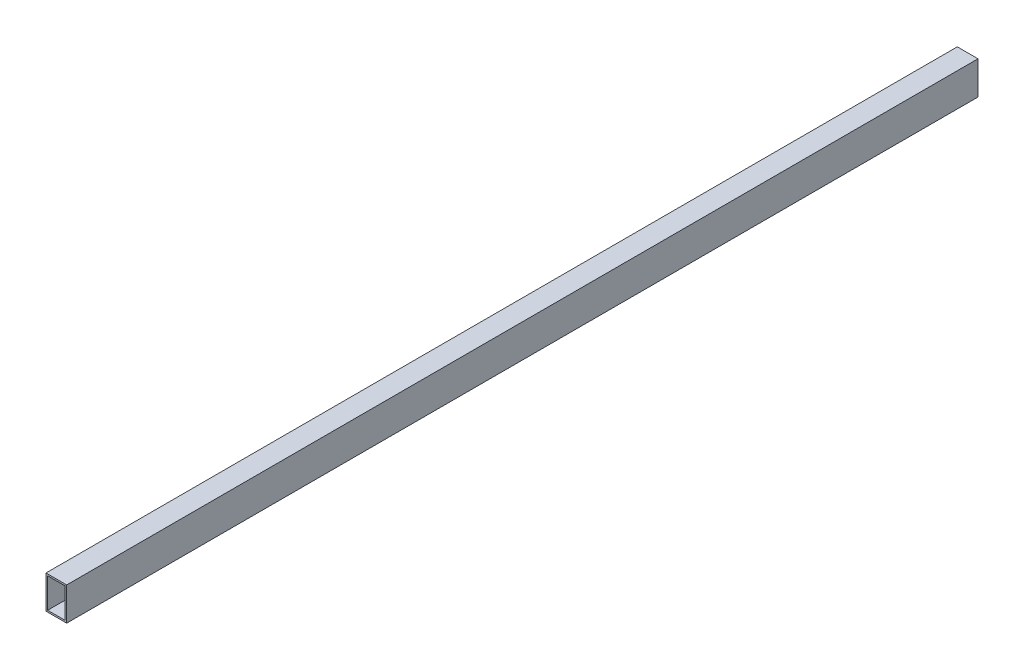
SolidWorks part; units mm, degrees
ref_plane "Front Plane" through (0, 0, 0) normal (0, 0, 1) x (1, 0, 0)
ref_plane "Top Plane" through (0, 0, 0) normal (0, 1, 0) x (1, 0, 0)
ref_plane "Right Plane" through (0, 0, 0) normal (1, 0, 0) x (0, 0, -1)
sketch "Sketch1" plane through (0, 0, 0) normal (0, 0, 1) x (1, 0, 0)
  line L1 (-25, 40) -> (25, 40)
  line L2 (-25, 40) -> (-25, -40)
  line L3 (-25, -40) -> (25, -40)
  line L4 (25, 40) -> (25, -40)
  point P0 (0, 0)
  point P7 (0, 0)
  dimension "D1" = 80
  dimension "D2" = 50
extrude "Boss-Extrude1" add sketch "Sketch1" along normal blind 2200 contours L1 L4 L3 L2
sketch "Sketch2" plane through (0, 0, 0) normal (0, 0, -1) x (-1, 0, 0)
  line L1 (-21, 36) -> (21, 36)
  line L2 (-21, 36) -> (-21, -36)
  line L3 (-21, -36) -> (21, -36)
  line L4 (21, 36) -> (21, -36)
  line L5 (-21, 36) -> (21, -36) construction
  line L6 (-21, -36) -> (21, 36) construction
  point P0 (0, 0)
  dimension "D1" = 42
  dimension "D2" = 72
extrude "Cut-Extrude1" cut sketch "Sketch2" against normal blind 2200
